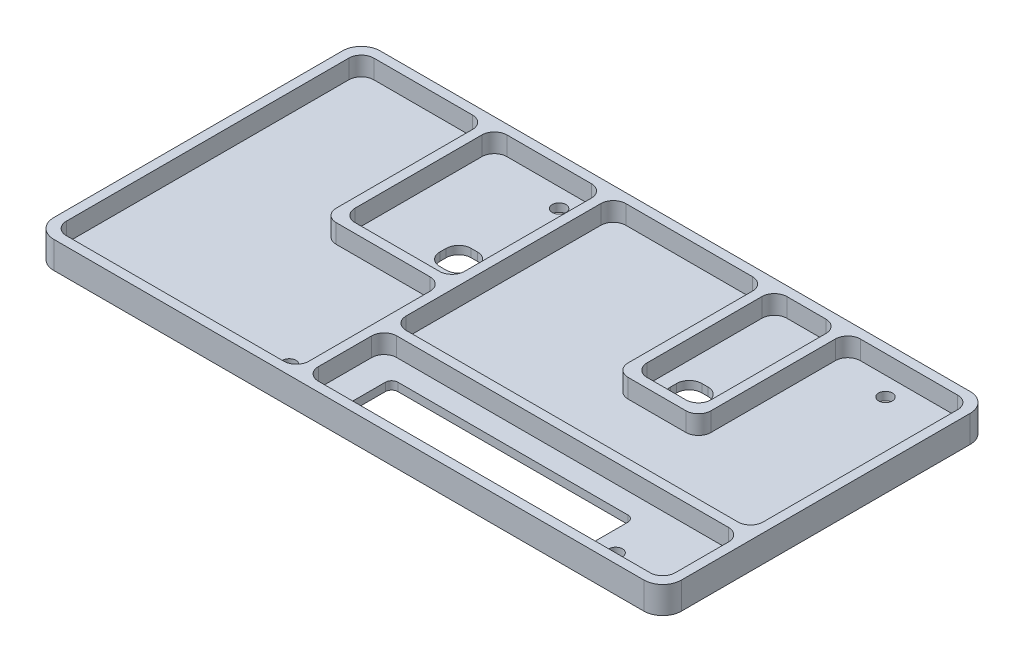
SolidWorks part; units mm, degrees
ref_plane "Front Plane" through (0, 0, 0) normal (0, 0, 1) x (1, 0, 0)
ref_plane "Top Plane" through (0, 0, 0) normal (0, 1, 0) x (1, 0, 0)
ref_plane "Right Plane" through (0, 0, 0) normal (1, 0, 0) x (0, 0, -1)
other "Configuration Table"
sketch "草图1" plane through (0, 0, 0) normal (0, 1, 0) x (1, 0, 0)
  line L1 (-48.8285, 31.982) -> (51.1715, 31.982)
  line L2 (-48.8285, 31.982) -> (-48.8285, -20.018)
  line L3 (-48.8285, -20.018) -> (51.1715, -20.018)
  line L4 (51.1715, 31.982) -> (51.1715, -20.018)
  dimension "D1" = 100
  dimension "D2" = 52
extrude "凸台-拉伸1" add sketch "草图1" along normal blind 8.6
sketch "草图2" plane through (0, 0, 0) normal (0, -1, 0) x (1, 0, 0)
  line L0 (51.1715, -31.982) -> (-48.8285, -31.982) construction
  line L1 (49.6715, -30.482) -> (-47.3285, -30.482)
  line L2 (49.6715, -30.482) -> (49.6715, 18.518)
  line L3 (49.6715, 18.518) -> (-47.3285, 18.518)
  line L4 (-47.3285, -30.482) -> (-47.3285, 18.518)
  line L5 (-48.8285, -31.982) -> (-48.8285, 20.018) construction
  line L6 (-48.8285, 20.018) -> (51.1715, 20.018) construction
  line L7 (51.1715, 20.018) -> (51.1715, -31.982) construction
  dimension "D1" = 1.5
  dimension "D2" = 1.5
  dimension "D3" = 1.5
  dimension "D4" = 1.5
extrude "切除-拉伸1" cut sketch "草图2" against normal blind 3
sketch "草图3" plane through (0, 3, 0) normal (0, -1, 0) x (1, 0, 0)
  line L0 (51.1715, -31.982) -> (-48.8285, -31.982) construction
  line L1 (35.9314, 9.319) -> (-2.7006, 9.319)
  line L2 (35.9314, 9.319) -> (35.9314, 16.7184)
  line L3 (35.9314, 16.7184) -> (-2.7006, 16.7184)
  line L4 (-2.7006, 9.319) -> (-2.7006, 16.7184)
  line L5 (-16.3285, -9.982) -> (-11.3285, -9.982)
  line L6 (-16.3285, -9.982) -> (-16.3285, -14.982)
  line L7 (-16.3285, -14.982) -> (-11.3285, -14.982)
  line L8 (-11.3285, -9.982) -> (-11.3285, -14.982)
  line L9 (-48.8285, -31.982) -> (-48.8285, 20.018) construction
  line L10 (48.159, -31.7129) -> (-45.8412, -31.7129) construction
  line L11 (20.6715, -9.7129) -> (25.6715, -9.7129)
  line L12 (20.6715, -9.7129) -> (20.6715, -14.7129)
  line L13 (20.6715, -14.7129) -> (25.6715, -14.7129)
  line L14 (25.6715, -9.7129) -> (25.6715, -14.7129)
  line L15 (51.1715, 20.018) -> (51.1715, -31.982) construction
  line L16 (-48.8285, 20.018) -> (51.1715, 20.018) construction
  circle A0 centre (-12.8285, 15.518) radius 1.1
  circle A1 centre (39.1715, 15.518) radius 1.1
  circle A2 centre (39.1715, -27.482) radius 1.1
  circle A3 centre (-12.8285, -27.482) radius 1.1
  dimension "D9" = 4.5
  dimension "D1" = 5
  dimension "D2" = 5
  dimension "D3" = 17
  dimension "D4" = 32.5
  dimension "D5" = 5
  dimension "D6" = 5
  dimension "D7" = 17
  dimension "D8" = 25.5
  dimension "D10" = 36
  dimension "D11" = 4.5
  dimension "D12" = 12
  dimension "D13" = 12
  dimension "D14" = 4.5
  dimension "D15" = 4.5
  dimension "D16" = 36
extrude "切除-拉伸2" cut sketch "草图3" against normal through all
sketch "草图8" plane through (0, 3, 0) normal (0, -1, 0) x (1, 0, 0)
  circle A0 centre (39.1715, -27.482) radius 2
  circle A1 centre (-12.8285, -27.482) radius 2
  circle A2 centre (-12.8285, 15.518) radius 2
  circle A3 centre (39.1715, 15.518) radius 2
fillet "圆角1" radius 2 8 edges at (25.6715, 5.8, -14.7129) (25.6715, 5.8, -9.7129) (20.6715, 5.8, -9.7129) (20.6715, 5.8, -14.7129) (-16.3285, 5.8, -14.982) (-11.3285, 5.8, -14.982) (-11.3285, 5.8, -9.982) (-16.3285, 5.8, -9.982)
sketch "草图4" plane through (0, 0, 0) normal (0, -1, 0) x (1, 0, 0)
  line L0 (51.1715, 20.018) -> (51.1715, -31.982) construction
  line L1 (51.1715, -2.482) -> (49.6715, -2.482)
  line L2 (51.1715, -2.482) -> (51.1715, 4.318)
  line L3 (51.1715, 4.318) -> (49.6715, 4.318)
  line L4 (49.6715, -2.482) -> (49.6715, 4.318)
  line L5 (49.6715, -30.482) -> (49.6715, 18.518) construction
  line L6 (51.1715, -31.982) -> (-48.8285, -31.982) construction
  dimension "D1" = 29.5
  dimension "D2" = 36.3
extrude "切除-拉伸3" cut sketch "草图4" against normal blind 1
sketch "草图5" plane through (0, 8.6, 0) normal (0, 1, 0) x (1, 0, 0)
  line L0 (51.1715, -20.018) -> (51.1715, 31.982) construction
  line L1 (-47.3285, 30.482) -> (49.6715, 30.482)
  line L2 (-47.3285, 30.482) -> (-47.3285, -18.518)
  line L3 (-47.3285, -18.518) -> (49.6715, -18.518)
  line L4 (49.6715, 30.482) -> (49.6715, -18.518)
  line L5 (-48.8285, -20.018) -> (51.1715, -20.018) construction
  line L6 (-48.8285, 31.982) -> (-48.8285, -20.018) construction
  line L7 (51.1715, 31.982) -> (-48.8285, 31.982) construction
  dimension "D1" = 1.5
  dimension "D2" = 1.5
  dimension "D3" = 1.5
  dimension "D4" = 1.5
extrude "切除-拉伸4" cut sketch "草图5" against normal blind 3
sketch "草图7" plane through (0, 5.6, 0) normal (0, 1, 0) x (1, 0, 0)
  line L0 (-8.6885, -18.518) -> (-8.6885, 4.782)
  line L1 (-47.3285, -18.518) -> (49.6715, -18.518) construction
  line L2 (-8.6885, 4.782) -> (-27.6285, 4.782)
  line L3 (-27.6285, 4.782) -> (-27.6285, 30.482)
  line L4 (49.6715, 30.482) -> (-47.3285, 30.482) construction
  line L5 (-27.6285, 30.482) -> (-26.1285, 30.482)
  line L6 (-26.1285, 30.482) -> (-26.1285, 6.282)
  line L7 (-26.1285, 6.282) -> (-8.6885, 6.282)
  line L8 (-8.6885, 6.282) -> (-8.6885, 30.482)
  line L9 (-8.6885, 30.482) -> (-7.1885, 30.482)
  line L10 (-7.1885, 30.482) -> (-7.1885, -4.518)
  line L11 (-7.1885, -4.518) -> (49.6715, -4.518)
  line L12 (49.6715, -18.518) -> (49.6715, 30.482) construction
  line L13 (49.6715, -4.518) -> (49.6715, -6.018)
  line L14 (49.6715, -6.018) -> (-7.1885, -6.018)
  line L15 (-7.1885, -6.018) -> (-7.1885, -18.518)
  line L16 (-7.1885, -18.518) -> (-8.6885, -18.518)
  line L17 (-48.8285, -20.018) -> (51.1715, -20.018) construction
  line L18 (51.1715, -20.018) -> (51.1715, 31.982) construction
  line L19 (51.1715, 31.982) -> (-48.8285, 31.982) construction
  line L20 (16.9715, 30.482) -> (16.9715, 6.682)
  line L21 (16.9715, 6.682) -> (30.1715, 6.682)
  line L22 (30.1715, 6.682) -> (30.1715, 30.482)
  line L23 (30.1715, 30.482) -> (28.6715, 30.482)
  line L24 (28.6715, 30.482) -> (28.6715, 8.182)
  line L25 (28.6715, 8.182) -> (18.4715, 8.182)
  line L26 (18.4715, 8.182) -> (18.4715, 30.482)
  line L27 (18.4715, 30.482) -> (16.9715, 30.482)
  dimension "D1" = 14
  dimension "D2" = 1.5
  dimension "D3" = 58.36
  dimension "D4" = 1.5
  dimension "D5" = 78.8
  dimension "D6" = 27.2
  dimension "D7" = 1.5
  dimension "D8" = 1.5
  dimension "D9" = 21
  dimension "D10" = 25.3
  dimension "D11" = 34.2
  dimension "D12" = 1.5
  dimension "D13" = 1.5
  dimension "D14" = 1.5
extrude "凸台-拉伸2" add sketch "草图7" along normal through all
fillet "圆角2" radius 3 4 edges at (51.1715, 4.3, 20.018) (51.1715, 4.3, -31.982) (-48.8285, 4.3, -31.982) (-48.8285, 4.3, 20.018)
fillet "圆角3" radius 2 30 edges at (-47.3285, 7.1, 18.518) (-47.3285, 7.1, -30.482) (49.6715, 7.1, -30.482) (49.6715, 7.1, 18.518) (49.6715, 1.5, -30.482) (49.6715, 1.5, 18.518) (-47.3285, 1.5, 18.518) (-47.3285, 1.5, -30.482) (-27.6285, 7.1, -4.782) (-27.6285, 7.1, -30.482) (-26.1285, 7.1, -30.482) (-26.1285, 7.1, -6.282) (-8.6885, 7.1, 18.518) (-8.6885, 7.1, -4.782) (-8.6885, 7.1, -6.282) (-8.6885, 7.1, -30.482) (-7.1885, 7.1, -30.482) (18.4715, 7.1, -8.182) (28.6715, 7.1, -8.182) (18.4715, 7.1, -30.482) (28.6715, 7.1, -30.482) (16.9715, 7.1, -30.482) (16.9715, 7.1, -6.682) (30.1715, 7.1, -6.682) (30.1715, 7.1, -30.482) (49.6715, 7.1, 4.518) (-7.1885, 7.1, 4.518) (-7.1885, 7.1, 6.018) (-7.1885, 7.1, 18.518) (49.6715, 7.1, 6.018)
fillet "圆角5" radius 1 4 edges at (35.9314, 4.3, 16.7184) (35.9314, 4.3, 9.319) (-2.7006, 4.3, 9.319) (-2.7006, 4.3, 16.7184)
sketch "草图9" plane through (51.1715, 0, 0) normal (1, 0, 0) x (0, 0, -1)
  line L0 (31.982, 8.6) -> (31.982, 0) construction
  line L1 (-20.018, 0) -> (31.982, 0)
  line L2 (-20.018, 0) -> (-20.018, 4.3)
  line L3 (-20.018, 4.3) -> (31.982, 4.3)
  line L4 (31.982, 0) -> (31.982, 4.3)
  point P7 (31.982, 0)
  point P9 (-20.018, 0)
extrude "切除-拉伸5" cut sketch "草图9" against normal through all
